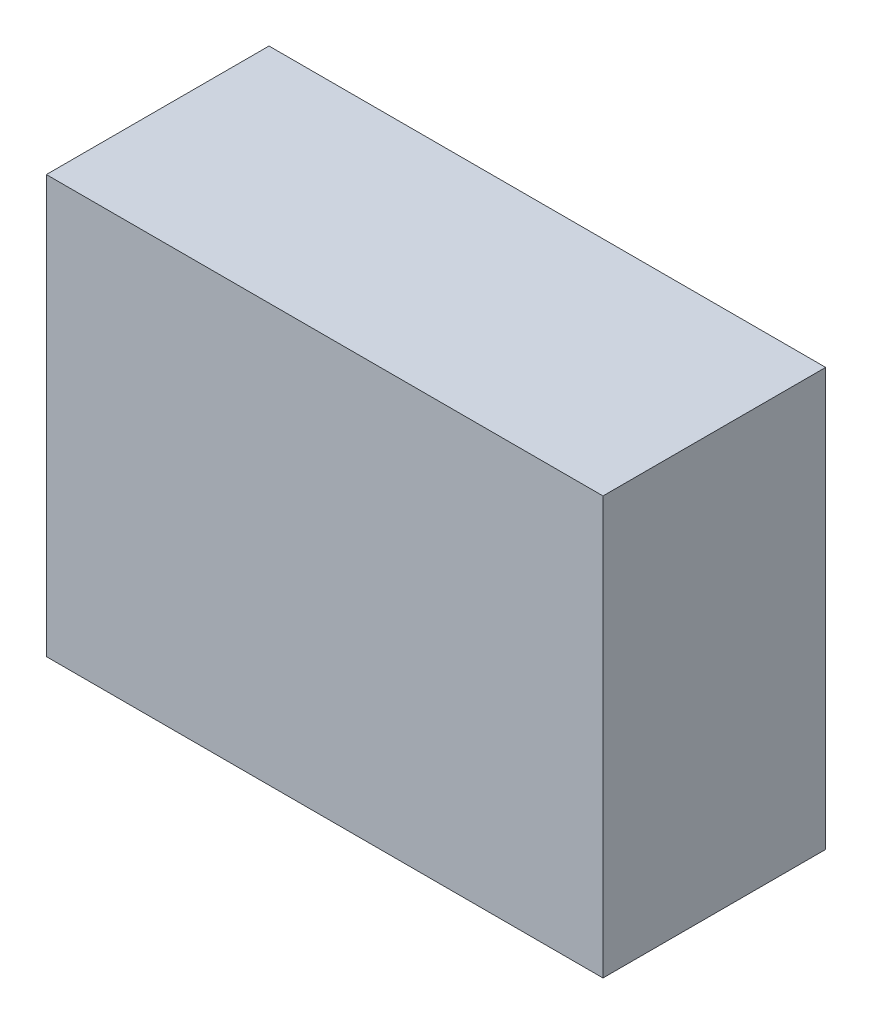
SolidWorks part; units mm, degrees
ref_plane "Спереди" through (0, 0, 0) normal (0, 0, 1) x (1, 0, 0)
ref_plane "Сверху" through (0, 0, 0) normal (0, 1, 0) x (1, 0, 0)
ref_plane "Справа" through (0, 0, 0) normal (1, 0, 0) x (0, 0, -1)
sketch "Эскиз1" plane through (0, 0, 0) normal (0, 0, 1) x (1, 0, 0)
  line L1 (-400, 300) -> (400, 300)
  line L2 (-400, 300) -> (-400, -300)
  line L3 (-400, -300) -> (400, -300)
  line L4 (400, 300) -> (400, -300)
  line L5 (-400, 300) -> (400, -300) construction
  line L6 (-400, -300) -> (400, 300) construction
  point P0 (0, 0)
extrude "Бобышка-Вытянуть1" add sketch "Эскиз1" along normal blind 320 contours L2 L1 L4 L3
sketch "Эскиз2" plane through (0, 0, 320) normal (0, 0, 1) x (1, 0, 0)
  line L0 (0, 300) -> (0, -300)
  line L1 (-400, 300) -> (400, 300) construction
  line L2 (-400, -300) -> (400, -300) construction
  line L3 (-400, 300) -> (-400, -300) construction
  line L4 (-400, -281.3218) -> (400, -281.3218)
  line L5 (400, 300) -> (400, -300) construction
